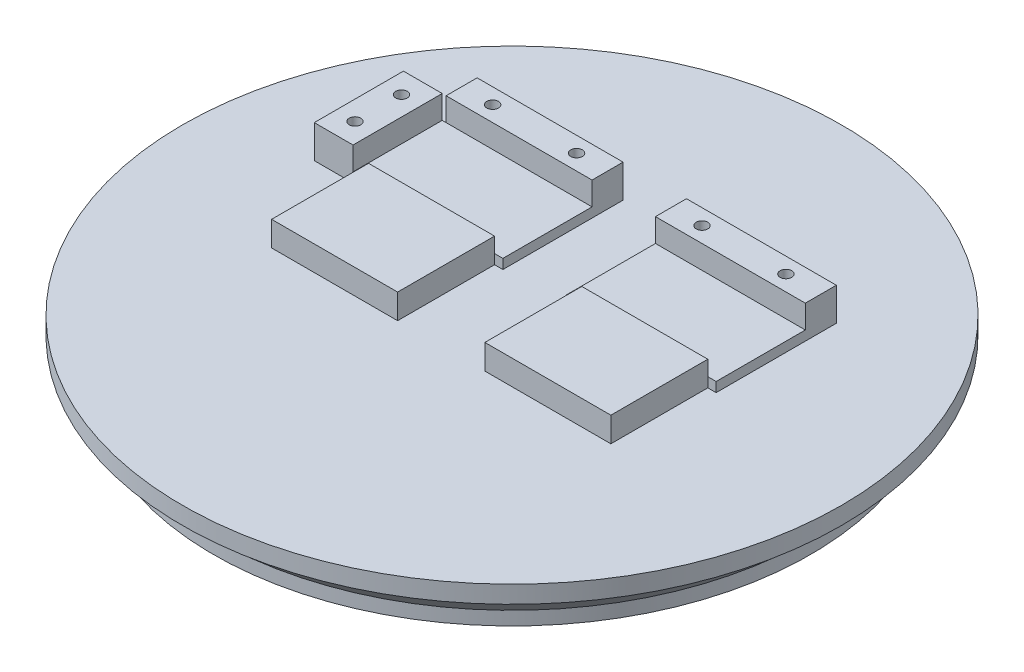
SolidWorks part; units mm, degrees
ref_plane "Front Plane" through (0, 0, 0) normal (0, 0, 1) x (1, 0, 0)
ref_plane "Top Plane" through (0, 0, 0) normal (0, 1, 0) x (1, 0, 0)
ref_plane "Right Plane" through (0, 0, 0) normal (1, 0, 0) x (0, 0, -1)
sketch "Sketch1" plane through (0, 0, 0) normal (0, 0, 1) x (1, 0, 0)
  line L0 (0, 12) -> (0, 15)
  line L1 (0, 15) -> (85, 15)
  line L2 (85, 15) -> (85, 10.5)
  line L3 (85, 10.5) -> (84, 10.5)
  line L4 (77, 3.5) -> (77, 0)
  line L5 (77, 0) -> (71, 0)
  line L6 (71, 0) -> (71, 12)
  line L7 (71, 12) -> (23.75, 12)
  line L8 (84, 10.5) -> (77, 3.5)
  line L9 (0, 12) -> (0, 9)
  line L10 (0, 9) -> (6.5, 9)
  line L11 (6.5, 9) -> (6.5, 6)
  line L12 (6.5, 6) -> (21.25, 6)
  line L13 (21.25, 6) -> (21.25, -7.5)
  line L15 (23.75, -7.5) -> (23.75, 12)
  line L16 (21.25, -7.5) -> (23.75, -7.5)
  point P6 (77, 10.5)
  dimension "D1" = 85
  dimension "D2" = 3
  dimension "D3" = 6
  dimension "D4" = 8
  dimension "D5" = 10.5
  dimension "D6" = 1.5
  dimension "D7" = 21.25
  dimension "D8" = 4.5
  dimension "D10" = 3
  dimension "D11" = 2.5
  dimension "D12" = 13.5
  dimension "D13" = 6.5
  dimension "D14" = 3
  dimension "D15" = 18
  dimension "D16" = 16.5
revolve "Revolve1" add sketch "Sketch1" angle 360 about L9
sketch "Sketch2" plane through (0, 12, 0) normal (0, -1, 0) x (1, 0, 0)
  line L1 (0, 70.2924) -> (-60.875, 35.1462)
  line L2 (-60.875, 35.1462) -> (-60.875, -35.1462)
  line L3 (-60.875, -35.1462) -> (0, -70.2924)
  line L4 (0, -70.2924) -> (60.875, -35.1462)
  line L5 (60.875, -35.1462) -> (60.875, 35.1462)
  line L6 (60.875, 35.1462) -> (0, 70.2924)
  circle A0 centre (0, 0) radius 71 construction
  circle A1 centre (0, 0) radius 71
  circle A2 centre (0, 0) radius 60.875 construction
  circle M8 centre (0, 0) radius 71
  dimension "D1" = 121.75
extrude "Boss-Extrude1" add sketch "Sketch2" along normal blind 11 contours L2 M8 | L1 M8 | L3 M8 | L4 M8 | L5 M8 | L6 M8
sketch "Sketch10" plane through (0, 15, 0) normal (0, 1, 0) x (1, 0, 0)
  line L0 (0, 99.1575) -> (0, -95.7853) construction
  line L1 (-99.194, 0) -> (98.9918, 0) construction
  line L2 (-55, 32) -> (-55, 9) construction
  line L3 (5, 9) -> (43.65, 9) construction
  line L4 (5, 9) -> (5, 32) construction
  line L5 (5, 32) -> (43.65, 32) construction
  line L6 (43.65, 9) -> (43.65, 32) construction
  line L7 (-50, 32) -> (-11.35, 32) construction
  line L8 (-50, 32) -> (-50, 9) construction
  line L9 (-50, 9) -> (-11.35, 9) construction
  line L10 (-11.35, 32) -> (-11.35, 9) construction
  line L11 (-50, 32) -> (-60, 32)
  line L12 (-50, 32) -> (-50, 9)
  line L13 (-50, 9) -> (-60, 9)
  line L14 (-60, 32) -> (-60, 9)
  line L15 (-50, 32) -> (-11.35, 32)
  line L16 (-50, 32) -> (-50, 40)
  line L17 (-50, 40) -> (-11.35, 40)
  line L18 (-11.35, 32) -> (-11.35, 40)
  line L19 (-50, 36) -> (-11.35, 36) construction
  line L20 (5, 32) -> (5, 40)
  line L21 (5, 36) -> (43.65, 36) construction
  line L22 (43.65, 32) -> (43.65, 40)
  line L23 (5, 32) -> (43.65, 32)
  line L24 (5, 40) -> (43.65, 40)
  line L25 (5, 32) -> (43.65, 32) construction
  line L26 (48.65, 32) -> (48.65, 9) construction
  line L27 (53.65, 32) -> (53.65, 9) construction
  line L28 (53.65, 32) -> (53.65, 9)
  line L29 (53.65, 32) -> (43.65, 32)
  line L30 (53.65, 9) -> (43.65, 9)
  line L31 (43.65, 32) -> (43.65, 9)
  line L32 (-49, 40) -> (-49, 32)
  line L33 (42.65, 40) -> (42.65, 32)
  circle A0 centre (-55, 26.5) radius 1.5
  circle A1 centre (-55, 14.5) radius 1.5
  circle A2 centre (-41, 36) radius 1.5
  circle A3 centre (-19.35, 36) radius 1.5
  circle A4 centre (13, 36) radius 1.5
  circle A5 centre (34.65, 36) radius 1.5
  circle A6 centre (48.65, 14.5) radius 1.5
  circle A7 centre (48.65, 26.5) radius 1.5
  dimension "D11" = 3
  dimension "D12" = 5.5
  dimension "D14" = 3
  dimension "D19" = 3
  dimension "D22" = 3
  dimension "D1" = 23
  dimension "D2" = 38.65
  dimension "D3" = 40
  dimension "D4" = 5
  dimension "D5" = 16.35
  dimension "D6" = 23
  dimension "D7" = 38.65
  dimension "D9" = 10
  dimension "D10" = 8
  dimension "D13" = 5.5
  dimension "D15" = 8
  dimension "D16" = 8
  dimension "D17" = 8
  dimension "D18" = 8
  dimension "D20" = 10
  dimension "D21" = 5.5
  dimension "D23" = 5.5
  dimension "D24" = 1
  dimension "D25" = 1
extrude "Boss-Extrude6" add sketch "Sketch10" along normal blind 8.5 contours L17 L32 L15 L18 A3 A2 | L11 L14 L13 L12 A1 A0 | L33 L24 L20 L23 A5 A4 | L24 L33 L23 L22
sketch "Sketch11" plane through (0, 15, 0) normal (0, 1, 0) x (1, 0, 0)
  line L0 (-50, 9) -> (-60, 9) construction
  line L1 (-50, 32) -> (-11.35, 32)
  line L2 (-50, 32) -> (-50, 9)
  line L3 (-50, 9) -> (-11.35, 9)
  line L4 (-11.35, 32) -> (-11.35, 9)
  line L5 (-11.35, 32) -> (-11.35, 40) construction
  line L6 (5, 32) -> (5, 40) construction
  line L7 (43.65, 32) -> (5, 32)
  line L8 (43.65, 32) -> (43.65, 9)
  line L9 (43.65, 9) -> (5, 9)
  line L10 (5, 32) -> (5, 9)
  line L12 (43.65, 32) -> (43.65, 40) construction
sketch "Sketch12" plane through (0, 12, 0) normal (0, -1, 0) x (1, 0, 0)
  circle A0 centre (0, 0) radius 57.5
  circle A1 centre (0, 0) radius 23.75 construction
  circle A2 centre (0, 0) radius 23.75
  dimension "D1" = 115
extrude "Cut-Extrude8" cut sketch "Sketch12" against normal blind 1
extrude "Boss-Extrude7" add sketch "Sketch11" along normal blind 2.5
sketch "Sketch14" plane through (0, 15, 0) normal (0, 1, 0) x (1, 0, 0)
  line L0 (43.65, 9) -> (43.65, 32) construction
  line L1 (43.65, 32) -> (5, 32) construction
  line L2 (5, 32) -> (5, 9) construction
  line L3 (5, 9) -> (43.65, 9) construction
  line L4 (-50, 32) -> (-50, 9) construction
  line L5 (-50, 9) -> (-11.35, 9) construction
  line L6 (-11.35, 9) -> (-11.35, 32) construction
  line L7 (-11.35, 32) -> (-49, 32) construction
  line L8 (-49, 32) -> (-50, 32) construction
  line L9 (43.65, 9) -> (43.65, 32)
  line L10 (43.65, 32) -> (5, 32)
  line L11 (5, 32) -> (5, 9)
  line L12 (5, 9) -> (43.65, 9)
  line L13 (-50, 32) -> (-50, 9)
  line L14 (-50, 9) -> (-11.35, 9)
  line L15 (-11.35, 9) -> (-11.35, 32)
  line L16 (-11.35, 32) -> (-49, 32)
  line L17 (-49, 32) -> (-50, 32)
  line L23 (-46, 9) -> (-13.5, 9)
  line L24 (-46, 9) -> (-46, -16)
  line L25 (-46, -16) -> (-13.5, -16)
  line L26 (-13.5, 9) -> (-13.5, -16)
  line L27 (9, 9) -> (41.5, 9)
  line L28 (9, 9) -> (9, -16)
  line L29 (9, -16) -> (41.5, -16)
  line L30 (41.5, 9) -> (41.5, -16)
  dimension "D1" = 32.5
  dimension "D2" = 32.5
  dimension "D3" = 2.15
  dimension "D4" = 2.15
  dimension "D5" = 25
extrude "Boss-Extrude8" add sketch "Sketch14" along normal blind 6.4 contours L26 L14 L24 L25 | L30 L12 L28 L29
